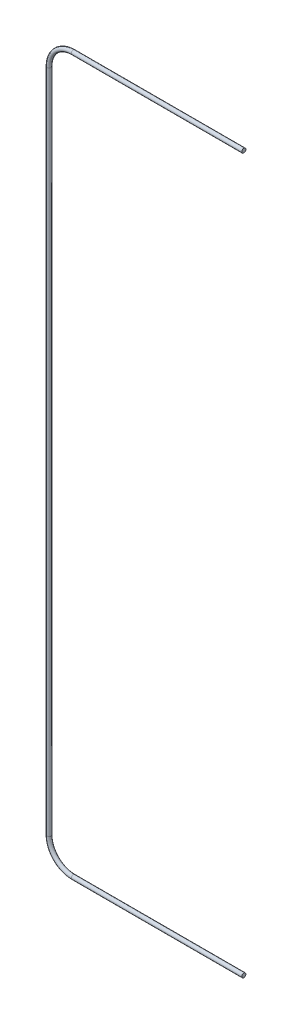
SolidWorks part; units mm, degrees
ref_plane "Front Plane" through (0, 0, 0) normal (0, 0, 1) x (1, 0, 0)
ref_plane "Top Plane" through (0, 0, 0) normal (0, 1, 0) x (1, 0, 0)
ref_plane "Right Plane" through (0, 0, 0) normal (1, 0, 0) x (0, 0, -1)
sketch "Sketch1" plane through (0, 0, 0) normal (0, 0, 1) x (1, 0, 0)
  line L0 (0, -1025) -> (0, 1025)
  line L1 (75, 1100) -> (600, 1100)
  line L2 (-416.9558, 0) -> (504.1592, 0) construction
  line L3 (75, -1100) -> (600, -1100)
  arc A0 (75, 1100) -> (0, 1025) centre (75, 1025) ccw
  arc A1 (75, -1100) -> (0, -1025) centre (75, -1025) cw
  point P6 (0, 1100)
  point P13 (0, 0)
  dimension "D3" = 75
  dimension "D1" = 1100
  dimension "D2" = 600
sweep "Sweep1" add path "Sketch1" circular profile diameter 12.7 parameters "D3"=12.7
